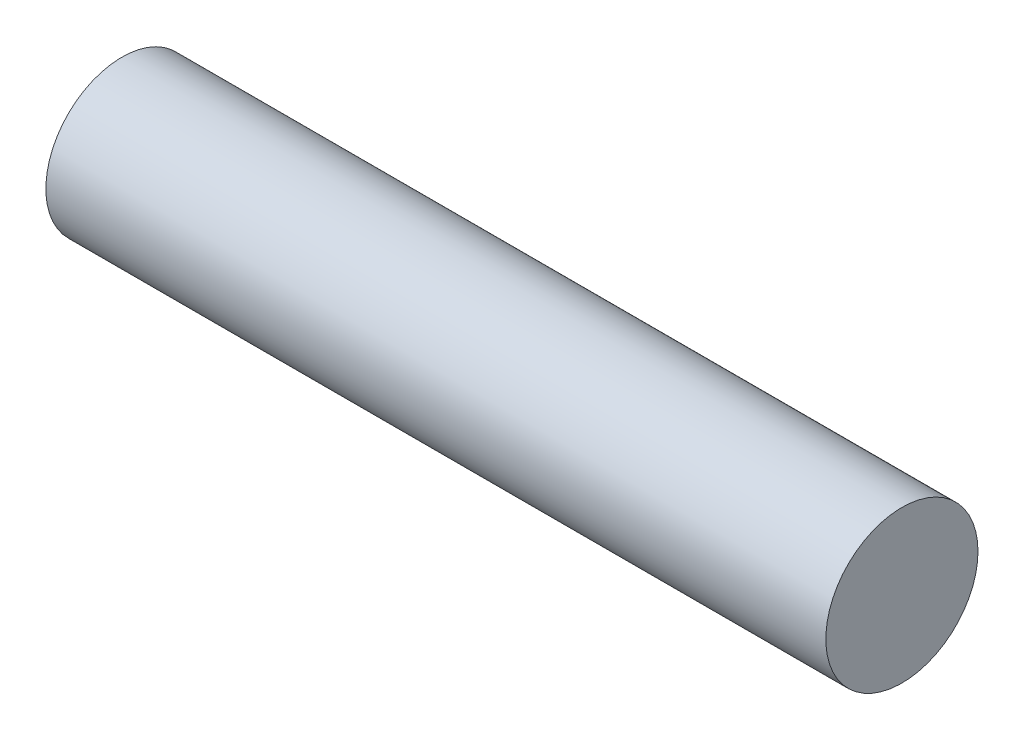
SolidWorks part; units mm, degrees
ref_plane "Front Plane" through (0, 0, 0) normal (0, 0, 1) x (1, 0, 0)
ref_plane "Top Plane" through (0, 0, 0) normal (0, 1, 0) x (1, 0, 0)
ref_plane "Right Plane" through (0, 0, 0) normal (1, 0, 0) x (0, 0, -1)
sketch "Sketch1" plane through (0, 0, 0) normal (1, 0, 0) x (0, 0, -1)
  circle A0 centre (0, 0) radius 101.6
  dimension "D1" = 203.2
extrude "Boss-Extrude1" add sketch "Sketch1" along normal blind 1041.4
